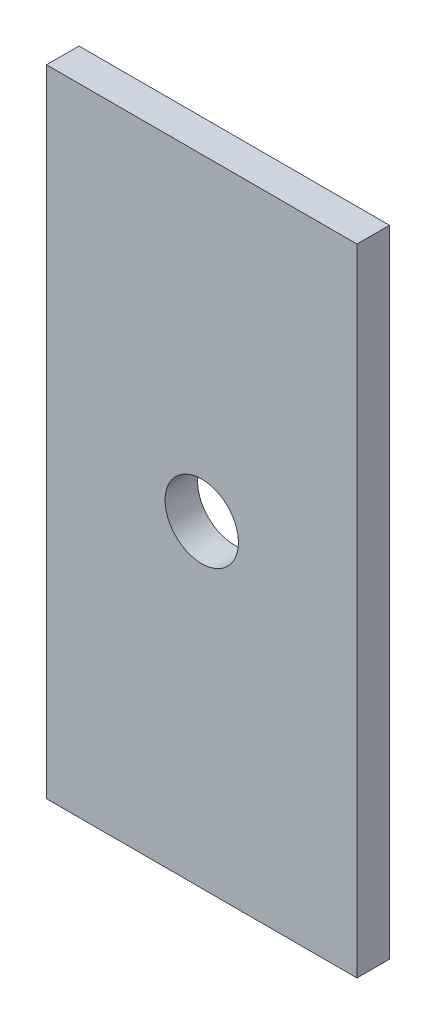
SolidWorks part; units mm, degrees
ref_plane "Front Plane" through (0, 0, 0) normal (0, 0, 1) x (1, 0, 0)
ref_plane "Top Plane" through (0, 0, 0) normal (0, 1, 0) x (1, 0, 0)
ref_plane "Right Plane" through (0, 0, 0) normal (1, 0, 0) x (0, 0, -1)
sketch "Sketch1" plane through (0, 0, 0) normal (0, 0, 1) x (1, 0, 0)
  line L1 (0, 0) -> (25.4, 0)
  line L2 (0, 0) -> (0, 52)
  line L3 (0, 52) -> (25.4, 52)
  line L4 (25.4, 0) -> (25.4, 52)
  dimension "D1" = 25.4
  dimension "D2" = 52
extrude "Boss-Extrude1" add sketch "Sketch1" along normal blind 2.66
sketch "Sketch2" plane through (0, 0, 0) normal (0, 0, -1) x (-1, 0, 0)
  circle A0 centre (-12.7, 26) radius 3
  dimension "D1" = 6
extrude "Cut-Extrude1" cut sketch "Sketch2" against normal blind 30
